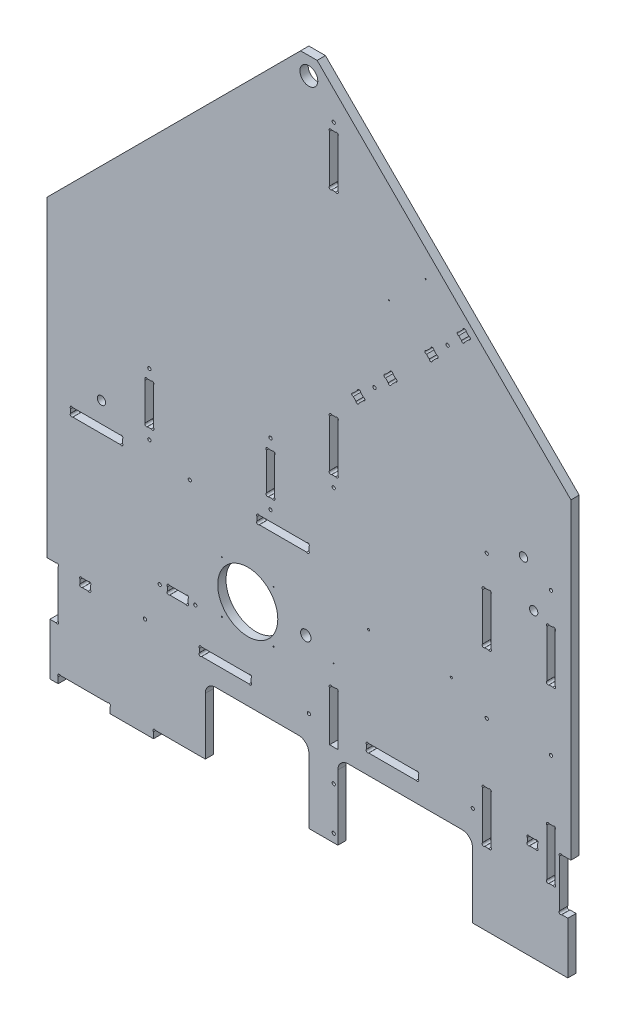
SolidWorks part; units mm, degrees
ref_plane "Plan de face" through (0, 0, 0) normal (0, 0, 1) x (1, 0, 0)
ref_plane "Plan de dessus" through (0, 0, 0) normal (0, 1, 0) x (1, 0, 0)
ref_plane "Plan de droite" through (0, 0, 0) normal (1, 0, 0) x (0, 0, -1)
sketch "Esquisse2" plane through (0, 0, 0) normal (0, 0, 1) x (1, 0, 0)
  line L0 (8, 626.5822) -> (-242, 376.5822) construction
  line L1 (-242, 376.5822) -> (-242, 76.5822) construction
  line L2 (-242, -23.4178) -> (258, -23.4178)
  line L3 (258, -23.4178) -> (258, 26.5822)
  line L4 (258, 376.5822) -> (8, 626.5822) construction
  line L5 (-268.5907, 76.5822) -> (316.4894, 76.5822) construction
  line L6 (-234, 74.4609) -> (-234, 28.7035)
  line L7 (-236.1213, 76.5822) -> (-242, 76.5822)
  line L8 (-236.1213, 26.5822) -> (-242, 26.5822)
  line L9 (-242, 26.5822) -> (-242, -23.4178)
  line L10 (-242, 76.5822) -> (-245, 76.5822)
  line L11 (252.1213, 26.5822) -> (258, 26.5822)
  line L12 (250, 74.4609) -> (250, 28.7035)
  line L13 (252.1213, 76.5822) -> (258, 76.5822)
  line L14 (258, 76.5822) -> (258, 376.5822) construction
  line L15 (-245, 76.5822) -> (-245, 377.8249)
  line L16 (8, 626.5822) -> (5.8787, 628.7035) construction
  line L17 (5.8787, 628.7035) -> (-245, 377.8249) construction
  line L18 (-245, 377.8249) -> (8, 630.8249)
  line L19 (258, 76.5822) -> (261, 76.5822)
  line L20 (261, 76.5822) -> (261, 377.8249)
  line L21 (8, 626.5822) -> (10.1213, 628.7035) construction
  line L22 (10.1213, 628.7035) -> (261, 377.8249) construction
  line L23 (261, 377.8249) -> (8, 630.8249)
  line L24 (-150, 274.5822) -> (-150, 234.5822) construction
  line L25 (-147.8787, 274.5822) -> (-144.1213, 274.5822)
  line L26 (-150, 272.4609) -> (-150, 236.7035)
  line L27 (-147.8787, 234.5822) -> (-144.1213, 234.5822)
  line L28 (-142, 272.4609) -> (-142, 236.7035)
  line L29 (-150, 274.5822) -> (-142, 274.5822) construction
  line L30 (-150, 234.5822) -> (-142, 234.5822) construction
  line L31 (-25, 274.5822) -> (-25, 234.5822) construction
  line L32 (-27.1213, 274.5822) -> (-30.8787, 274.5822)
  line L33 (-25, 272.4609) -> (-25, 236.7035)
  line L34 (-27.1213, 234.5822) -> (-30.8787, 234.5822)
  line L35 (-33, 272.4609) -> (-33, 236.7035)
  line L36 (-33, 274.5822) -> (-33, 234.5822) construction
  line L37 (163.925, 463.9178) -> (120.0844, 431.3909) construction
  line L38 (49.3737, 360.6803) -> (93.2143, 393.2072) construction
  line L39 (245.7307, 212.5822) -> (237.7307, 96.5822) construction
  line L40 (183.7307, 212.5822) -> (175.7307, 96.5822) construction
  line L41 (223.0384, 268.2822) -> (227.1201, 266.2822) construction
  arc A0 (-234, 74.4609) -> (-236.1213, 76.5822) centre (-235.0607, 75.5216) ccw
  arc A1 (-236.1213, 26.5822) -> (-234, 28.7035) centre (-235.0607, 27.6429) ccw
  arc A2 (252.1213, 26.5822) -> (250, 28.7035) centre (251.0607, 27.6429) cw
  arc A3 (250, 74.4609) -> (252.1213, 76.5822) centre (251.0607, 75.5216) cw
  arc A4 (-27.1213, 234.5822) -> (-25, 236.7035) centre (-26.0607, 235.6429) ccw
  arc A5 (-25, 272.4609) -> (-27.1213, 274.5822) centre (-26.0607, 273.5216) ccw
  arc A6 (-30.8787, 274.5822) -> (-33, 272.4609) centre (-31.9393, 273.5216) ccw
  arc A7 (-33, 236.7035) -> (-30.8787, 234.5822) centre (-31.9393, 235.6429) ccw
  arc A8 (-147.8787, 274.5822) -> (-150, 272.4609) centre (-148.9393, 273.5216) ccw
  arc A9 (-144.1213, 234.5822) -> (-142, 236.7035) centre (-143.0607, 235.6429) ccw
  arc A10 (-150, 236.7035) -> (-147.8787, 234.5822) centre (-148.9393, 235.6429) ccw
  arc A11 (-142, 272.4609) -> (-144.1213, 274.5822) centre (-143.0607, 273.5216) ccw
  circle A12 centre (-29, 284.5822) radius 1.55
  circle A13 centre (-29, 224.5822) radius 1.55
  circle A14 centre (-146, 284.0822) radius 1.55
  circle A15 centre (-146, 224.5822) radius 1.55
  circle A16 centre (-101.6159, 108.5822) radius 1.55
  circle A17 centre (-136, 108.5822) radius 1.55
  circle A19 centre (225.0793, 267.2822) radius 4
  circle A23 centre (142.0047, 447.6544) radius 1.55
  circle A24 centre (71.294, 376.9437) radius 1.55
  circle A29 centre (241.7307, 154.5822) radius 1.55
  circle A30 centre (179.7307, 154.5822) radius 1.55
  dimension "D2" = 650
  dimension "D4" = 50
  dimension "D6" = 1.5
  dimension "D7" = 1.5
  dimension "D1" = 100
  dimension "D3" = 500
  dimension "D8" = 8
  dimension "D9" = 8
  dimension "D10" = 0
  dimension "D11" = 0
  dimension "D12" = 0
  dimension "D13" = 0
  dimension "D14" = 0
extrude "Boss.-Extru.1" add sketch "Esquisse2" along normal blind 8
sketch "Esquisse3" plane through (0, 0, 8) normal (0, 0, 1) x (1, 0, 0)
  line L0 (-117, 501.5822) -> (8, 376.5822) construction
  line L1 (25.7058, 481.3683) -> (25.7058, 606.6018) construction
  line L2 (30, 604.6018) -> (30, 596.1432) construction
  line L3 (8, 630.8249) -> (8, -42.6778) construction
  line L4 (121.6863, 497.3396) -> (-14.463, 361.1903) construction
  line L5 (158.8094, 475.7728) -> (106.9524, 423.9159) construction
  line L6 (106.9524, 423.9159) -> (44.0813, 361.0447) construction
  line L7 (44.0813, 361.0447) -> (16.8577, 388.2684) construction
  line L8 (136.0178, 441.6675) -> (53.2863, 358.936) construction
  line L9 (50.4578, 361.7644) -> (56.1147, 356.1076) construction
  line L10 (136.0178, 441.6675) -> (164.4663, 470.116) construction
  line L11 (138.8462, 438.8391) -> (56.1147, 356.1076) construction
  line L12 (138.8462, 438.8391) -> (167.2947, 467.2875) construction
  line L13 (50.4578, 361.7644) -> (161.6378, 472.9444) construction
  line L14 (124.2412, 427.2341) -> (121.5844, 429.8909)
  line L15 (162.425, 462.4178) -> (158.3539, 458.3468)
  line L16 (155.3539, 458.3468) -> (152.6971, 461.0036)
  line L17 (144.8331, 444.826) -> (136.3478, 453.3112) construction
  line L18 (152.6971, 464.0036) -> (156.7681, 468.0747)
  line L19 (159.7681, 468.0747) -> (162.425, 465.4178)
  line L20 (125.6554, 436.962) -> (121.5844, 432.8909)
  line L21 (131.3123, 434.3051) -> (128.6554, 436.962)
  line L22 (127.2412, 427.2341) -> (131.3123, 431.3051)
  line L23 (65.6371, 382.6006) -> (74.1224, 374.1153) construction
  line L24 (56.5305, 356.5234) -> (60.6016, 360.5945)
  line L25 (84.6432, 387.6361) -> (81.9864, 390.2929)
  line L26 (81.9864, 393.2929) -> (86.0574, 397.364)
  line L27 (89.0574, 397.364) -> (91.7143, 394.7072)
  line L28 (0, 622.8249) -> (16, 622.8249)
  line L29 (8, 630.8249) -> (-245, 377.8249) construction
  line L30 (16, 622.8249) -> (8, 630.8249)
  line L31 (49.5, 481.3683) -> (-92.9948, 481.3683) construction
  line L32 (36, 509.4867) -> (36, 448.3117) construction
  line L33 (91.7143, 391.7072) -> (87.6432, 387.6361)
  line L34 (50.8737, 359.1803) -> (53.5305, 356.5234)
  line L35 (54.9447, 366.2513) -> (50.8737, 362.1803)
  line L36 (60.6016, 363.5945) -> (57.9447, 366.2513)
  line L37 (36, -23.4178) -> (36, 39.5822)
  line L38 (-234, -15.4178) -> (-112, -15.4178) construction
  line L39 (46, 49.5822) -> (156, 49.5822)
  line L40 (166, 39.5822) -> (166, -23.4178)
  line L41 (-242, -23.4178) -> (258, -23.4178) construction
  line L42 (166, -23.4178) -> (36, -23.4178)
  line L43 (245.7307, 46.5822) -> (245.7307, 260.1538) construction
  line L44 (245.7307, 302.5822) -> (175.7307, 302.5822) construction
  line L45 (175.7307, 302.5822) -> (175.7307, 46.5822) construction
  line L46 (36, -23.4178) -> (28, -23.4178) construction
  line L47 (-234, 156.5822) -> (-234, -15.4178) construction
  line L48 (16.8577, 388.2684) -> (133.7071, 505.1178) construction
  line L49 (-112, -15.4178) -> (-112, 156.5822) construction
  line L50 (8, -23.4178) -> (8, 39.5822)
  line L51 (-2, 49.5822) -> (-82, 49.5822)
  line L52 (-92, 39.5822) -> (-92, -15.4178)
  line L53 (-92, -23.4178) -> (8, -23.4178)
  line L54 (28, -23.4178) -> (28, 596.1432) construction
  line L55 (36, 521.5822) -> (28, 521.5822) construction
  line L56 (36, 446.5822) -> (28, 446.5822) construction
  line L57 (36, 381.5822) -> (28, 381.5822) construction
  line L58 (149.3825, 499.5799) -> (-10.1278, 340.0696) construction
  line L59 (28, 56.5822) -> (36, 56.5822)
  line L60 (28, 56.5822) -> (28, 104.4609)
  line L61 (30.1213, 106.5822) -> (33.714, 106.5822)
  line L62 (36, 104.4609) -> (36, 56.5822)
  line L63 (28, 106.5822) -> (31.8505, 102.7317) construction
  line L64 (31.8505, 102.7317) -> (36, 106.5822) construction
  line L65 (30.1213, 521.5822) -> (33.8787, 521.5822)
  line L66 (36, 523.7035) -> (36, 569.4609)
  line L67 (33.8787, 571.5822) -> (30.1213, 571.5822)
  line L68 (28, 569.4609) -> (28, 523.7035)
  line L69 (36, 283.5822) -> (28, 283.5822) construction
  line L70 (30.1213, 283.5822) -> (33.8787, 283.5822)
  line L71 (36, 285.7035) -> (36, 331.4609)
  line L72 (33.8787, 333.5822) -> (30.1213, 333.5822)
  line L73 (28, 331.4609) -> (28, 285.7035)
  line L74 (28, 333.5822) -> (32, 333.5822) construction
  line L75 (175.7307, 46.5822) -> (245.7307, 46.5822) construction
  line L76 (242.7592, 46.5822) -> (240.7023, 46.5822) construction
  line L77 (245.7307, 48.7035) -> (245.7307, 94.4609) construction
  line L78 (210.7307, 212.5822) -> (175.7307, 212.5822) construction
  line L79 (243.6094, 212.5822) -> (239.8521, 212.5822)
  line L80 (220.9721, 76.5822) -> (226.7294, 76.5822)
  line L81 (218.8507, 74.4609) -> (218.8507, 70.7035)
  line L82 (237.7307, 218.4818) -> (237.7307, 262.5822) construction
  line L83 (240.7592, 266.3605) -> (244.5166, 266.3605) construction
  line L84 (245.7307, 260.1538) -> (245.7307, 218.4818) construction
  line L85 (210.7307, 302.5822) -> (210.7307, 46.5822) construction
  line L86 (239.8521, 262.5822) -> (243.3024, 262.5822)
  line L87 (181.6094, 212.5822) -> (177.8521, 212.5822)
  line L88 (237.7307, 260.4609) -> (237.7307, 214.7035)
  line L89 (220.9721, 68.5822) -> (226.7294, 68.5822)
  line L90 (228.8507, 74.4609) -> (228.8507, 70.7035)
  line L91 (-192.25, 227.5756) -> (-192.25, 260.1538) construction
  line L92 (175.7307, 48.7035) -> (175.7307, 94.4609) construction
  line L93 (178.7023, 46.5822) -> (180.7592, 46.5822) construction
  line L94 (179.7307, 302.5822) -> (179.7307, 46.5822) construction
  line L95 (241.7307, 46.5822) -> (241.7307, 302.5822) construction
  line L96 (245.7307, 260.1538) -> (245.7307, 214.7035)
  line L97 (175.7307, 260.1538) -> (175.7307, 214.7035)
  line L98 (181.6094, 262.5822) -> (178.1591, 262.5822)
  line L99 (183.7307, 260.4609) -> (183.7307, 214.7035)
  line L100 (179.7307, 174.5822) -> (241.7307, 174.5822) construction
  line L101 (32, -23.4178) -> (32, 596.1432) construction
  line L102 (-234, 156.5822) -> (-234, 164.5822) construction
  line L103 (-234, 164.5822) -> (-112, 164.5822) construction
  line L104 (-112, 164.5822) -> (-112, 156.5822) construction
  line L105 (261, 76.5822) -> (-245, 76.5822) construction
  line L106 (261, 377.8249) -> (8, 630.8249) construction
  line L107 (-222, 212.4609) -> (-222, 208.7035)
  line L108 (-219.8787, 214.5822) -> (-174.1213, 214.5822)
  line L109 (-172, 212.4609) -> (-172, 208.7035)
  line L110 (-174.1213, 206.5822) -> (-219.8787, 206.5822)
  line L111 (8, 212.4609) -> (8, 208.7035)
  line L112 (5.8787, 214.5822) -> (-39.8787, 214.5822)
  line L113 (-42, 212.4609) -> (-42, 208.7035)
  line L114 (-39.8787, 206.5822) -> (5.8787, 206.5822)
  line L115 (-76, 166.5822) -> (-76, 106.5822) construction
  line L116 (-234, -23.4178) -> (-234, -17.5391)
  line L117 (-231.8787, -15.4178) -> (-186.1213, -15.4178)
  line L118 (-184, -17.5391) -> (-184, -23.4178)
  line L119 (-242, 26.5822) -> (-242, -23.4178) construction
  line L120 (-92, -15.4178) -> (-139.8787, -15.4178)
  line L121 (-142, -17.5391) -> (-142, -23.4178)
  line L122 (-142, -23.4178) -> (-92, -23.4178)
  line L123 (-184, -23.4178) -> (-234, -23.4178)
  line L124 (-81, 136.5822) -> (-21, 136.5822) construction
  line L125 (-81, 166.5822) -> (-21, 166.5822) construction
  line L126 (-81, 166.5822) -> (-81, 106.5822) construction
  line L127 (-81, 106.5822) -> (-21, 106.5822) construction
  line L128 (-21, 166.5822) -> (-21, 106.5822) construction
  line L129 (-51, 166.5822) -> (-51, 106.5822) construction
  line L130 (-81, 161.5822) -> (-21, 161.5822) construction
  line L131 (28, 596.1432) -> (28, 606.6018) construction
  line L132 (28, 596.1432) -> (32, 596.1432) construction
  line L133 (32, 596.1432) -> (32, 602.6018) construction
  line L134 (8, 630.8249) -> (8, 580.8249) construction
  line L135 (32, 602.6018) -> (28, 606.6018) construction
  line L136 (65.7875, 76.5822) -> (111.5449, 76.5822)
  line L137 (113.6662, 74.4609) -> (113.6662, 70.7035)
  line L138 (111.5449, 68.5822) -> (65.7875, 68.5822)
  line L139 (63.6662, 70.7035) -> (63.6662, 74.4609)
  line L140 (-47.6662, 70.7035) -> (-47.6662, 74.4609)
  line L141 (-95.5449, 68.5822) -> (-49.7875, 68.5822)
  line L142 (-97.6662, 74.4609) -> (-97.6662, 70.7035)
  line L143 (-49.7875, 76.5822) -> (-95.5449, 76.5822)
  line L144 (-212.8507, 74.4609) -> (-212.8507, 70.7035)
  line L145 (220.9721, 76.5822) -> (226.7294, 76.5822) construction
  line L146 (218.8507, 74.4609) -> (218.8507, 70.7035) construction
  line L147 (220.9721, 68.5822) -> (226.7294, 68.5822) construction
  line L148 (228.8507, 74.4609) -> (228.8507, 70.7035) construction
  line L149 (-204.9721, 68.5822) -> (-210.7294, 68.5822)
  line L150 (-202.8507, 74.4609) -> (-202.8507, 70.7035)
  line L151 (-204.9721, 76.5822) -> (-210.7294, 76.5822)
  line L152 (-245, 377.8249) -> (-245, 76.5822) construction
  line L153 (-172, 210.5822) -> (-42, 210.5822) construction
  line L154 (-202.8507, 72.5822) -> (-97.6662, 72.5822) construction
  line L155 (-97.6662, 72.5822) -> (-47.6662, 72.5822) construction
  line L156 (-47.6662, 72.5822) -> (63.6662, 72.5822) construction
  line L157 (63.6662, 72.5822) -> (218.8507, 72.5822) construction
  line L158 (8, 630.8249) -> (0, 622.8249)
  line L159 (181.6094, 46.5822) -> (177.8521, 46.5822)
  line L160 (239.8521, 96.5822) -> (243.6094, 96.5822)
  line L161 (237.7307, 94.4609) -> (237.7307, 48.7035)
  line L162 (239.8521, 46.5822) -> (243.6094, 46.5822)
  line L163 (245.7307, 94.4609) -> (245.7307, 48.7035)
  line L164 (175.7307, 94.4609) -> (175.7307, 48.7035)
  line L165 (181.6094, 96.5822) -> (177.8521, 96.5822)
  line L166 (183.7307, 94.4609) -> (183.7307, 48.7035)
  line L167 (245.7307, 262.5822) -> (245.7307, 302.5822) construction
  line L168 (-95.2925, 112.5822) -> (-106.3787, 112.5822) construction
  line L169 (-126.3787, 112.5822) -> (-110.6213, 112.5822)
  line L170 (-128.5, 110.4609) -> (-128.5, 106.7035)
  line L171 (-126.3787, 104.5822) -> (-110.6213, 104.5822)
  line L172 (-108.5, 110.4609) -> (-108.5, 106.7035)
  line L173 (-143.5, 112.5822) -> (-143.5, 104.5822) construction
  arc A0 (159.7681, 468.0747) -> (156.7681, 468.0747) centre (158.2681, 468.0747) ccw
  arc A1 (162.425, 465.4178) -> (162.425, 462.4178) centre (162.425, 463.9178) cw
  arc A2 (152.6971, 464.0036) -> (152.6971, 461.0036) centre (152.6971, 462.5036) ccw
  arc A3 (155.3539, 458.3468) -> (158.3539, 458.3468) centre (156.8539, 458.3468) ccw
  arc A4 (131.3123, 434.3051) -> (131.3123, 431.3051) centre (131.3123, 432.8051) cw
  arc A5 (125.6554, 436.962) -> (128.6554, 436.962) centre (127.1554, 436.962) cw
  arc A6 (121.5844, 432.8909) -> (121.5844, 429.8909) centre (121.5844, 431.3909) ccw
  arc A7 (127.2412, 427.2341) -> (124.2412, 427.2341) centre (125.7412, 427.2341) cw
  arc A8 (89.0574, 397.364) -> (86.0574, 397.364) centre (87.5574, 397.364) ccw
  arc A9 (91.7143, 391.7072) -> (91.7143, 394.7072) centre (91.7143, 393.2072) ccw
  arc A10 (81.9864, 393.2929) -> (81.9864, 390.2929) centre (81.9864, 391.7929) ccw
  arc A11 (84.6432, 387.6361) -> (87.6432, 387.6361) centre (86.1432, 387.6361) ccw
  arc A12 (60.6016, 363.5945) -> (60.6016, 360.5945) centre (60.6016, 362.0945) cw
  arc A13 (54.9447, 366.2513) -> (57.9447, 366.2513) centre (56.4447, 366.2513) cw
  arc A14 (56.5305, 356.5234) -> (53.5305, 356.5234) centre (55.0305, 356.5234) cw
  arc A15 (50.8737, 359.1803) -> (50.8737, 362.1803) centre (50.8737, 360.6803) cw
  circle A16 centre (120.815, 492.2256) radius 0.5
  circle A17 centre (85.4596, 456.8703) radius 0.5
  circle A18 centre (65.4807, 171.5822) radius 1
  arc A19 (30.1213, 106.5822) -> (28, 104.4609) centre (29.0607, 105.5216) ccw
  arc A20 (36, 104.4609) -> (33.714, 106.5822) centre (34.857, 105.5216) ccw
  arc A21 (30.1213, 571.5822) -> (28, 569.4609) centre (29.0607, 570.5216) ccw
  arc A22 (36, 569.4609) -> (33.8787, 571.5822) centre (34.9393, 570.5216) ccw
  arc A23 (28, 523.7035) -> (30.1213, 521.5822) centre (29.0607, 522.6429) ccw
  arc A24 (33.8787, 521.5822) -> (36, 523.7035) centre (34.9393, 522.6429) ccw
  arc A25 (30.1213, 333.5822) -> (28, 331.4609) centre (29.0607, 332.5216) ccw
  arc A26 (36, 331.4609) -> (33.8787, 333.5822) centre (34.9393, 332.5216) ccw
  arc A27 (28, 285.7035) -> (30.1213, 283.5822) centre (29.0607, 284.6429) ccw
  arc A28 (33.8787, 283.5822) -> (36, 285.7035) centre (34.9393, 284.6429) ccw
  arc A29 (239.8521, 262.5822) -> (237.7307, 260.4609) centre (238.7914, 261.5216) ccw
  arc A30 (245.7307, 260.1538) -> (243.3024, 262.5822) centre (244.5166, 261.368) ccw
  arc A31 (237.7307, 214.7035) -> (239.8521, 212.5822) centre (238.7914, 213.6429) ccw
  arc A32 (243.6094, 212.5822) -> (245.7307, 214.7035) centre (244.6701, 213.6429) ccw
  arc A33 (181.6094, 262.5822) -> (183.7307, 260.4609) centre (182.6701, 261.5216) cw
  arc A34 (175.7307, 260.1538) -> (178.1591, 262.5822) centre (176.9449, 261.368) cw
  arc A35 (177.8521, 212.5822) -> (175.7307, 214.7035) centre (176.7914, 213.6429) cw
  arc A36 (183.7307, 214.7035) -> (181.6094, 212.5822) centre (182.6701, 213.6429) cw
  arc A37 (245.7307, 94.4609) -> (243.6094, 96.5822) centre (244.6701, 95.5216) ccw
  arc A38 (239.8521, 96.5822) -> (237.7307, 94.4609) centre (238.7914, 95.5216) ccw
  arc A39 (237.7307, 48.7035) -> (239.8521, 46.5822) centre (238.7914, 47.6429) ccw
  arc A40 (243.6094, 46.5822) -> (245.7307, 48.7035) centre (244.6701, 47.6429) ccw
  arc A41 (175.7307, 94.4609) -> (177.8521, 96.5822) centre (176.7914, 95.5216) cw
  arc A42 (181.6094, 96.5822) -> (183.7307, 94.4609) centre (182.6701, 95.5216) cw
  arc A43 (177.8521, 46.5822) -> (175.7307, 48.7035) centre (176.7914, 47.6429) cw
  arc A44 (183.7307, 48.7035) -> (181.6094, 46.5822) centre (182.6701, 47.6429) cw
  circle A45 centre (179.7307, 292.5822) radius 1.55
  circle A46 centre (241.7307, 292.5822) radius 1.55
  circle A47 centre (179.7307, 174.5822) radius 0.5 construction
  circle A48 centre (241.7307, 174.5822) radius 0.5 construction
  circle A49 centre (32, 126.5822) radius 0.5
  circle A50 centre (32, 579.0822) radius 1.55
  circle A51 centre (32, 25.9979) radius 1.55
  circle A52 centre (32, -15.4178) radius 1.55
  arc A53 (-219.8787, 214.5822) -> (-222, 212.4609) centre (-220.9393, 213.5216) ccw
  arc A54 (-222, 208.7035) -> (-219.8787, 206.5822) centre (-220.9393, 207.6429) ccw
  arc A55 (-174.1213, 206.5822) -> (-172, 208.7035) centre (-173.0607, 207.6429) ccw
  arc A56 (-172, 212.4609) -> (-174.1213, 214.5822) centre (-173.0607, 213.5216) ccw
  arc A57 (-39.8787, 214.5822) -> (-42, 212.4609) centre (-40.9393, 213.5216) ccw
  arc A58 (8, 212.4609) -> (5.8787, 214.5822) centre (6.9393, 213.5216) ccw
  arc A59 (5.8787, 206.5822) -> (8, 208.7035) centre (6.9393, 207.6429) ccw
  arc A60 (-42, 208.7035) -> (-39.8787, 206.5822) centre (-40.9393, 207.6429) ccw
  arc A61 (-231.8787, -15.4178) -> (-234, -17.5391) centre (-232.9393, -16.4784) ccw
  arc A62 (-184, -17.5391) -> (-186.1213, -15.4178) centre (-185.0607, -16.4784) ccw
  arc A63 (-139.8787, -15.4178) -> (-142, -17.5391) centre (-140.9393, -16.4784) ccw
  circle A64 centre (-51, 136.5822) radius 29
  circle A65 centre (-76, 161.5822) radius 0.5
  circle A66 centre (-26, 161.5822) radius 0.5
  circle A67 centre (-26, 111.5822) radius 0.5
  circle A68 centre (-76, 111.5822) radius 0.5
  circle A69 centre (5, 136.5822) radius 5
  circle A70 centre (8, 605.8249) radius 8.625
  arc A71 (63.6662, 70.7035) -> (65.7875, 68.5822) centre (64.7269, 69.6429) ccw
  arc A72 (65.7875, 76.5822) -> (63.6662, 74.4609) centre (64.7269, 75.5216) ccw
  arc A73 (113.6662, 74.4609) -> (111.5449, 76.5822) centre (112.6055, 75.5216) ccw
  arc A74 (111.5449, 68.5822) -> (113.6662, 70.7035) centre (112.6055, 69.6429) ccw
  arc A75 (-95.5449, 68.5822) -> (-97.6662, 70.7035) centre (-96.6055, 69.6429) cw
  arc A76 (-97.6662, 74.4609) -> (-95.5449, 76.5822) centre (-96.6055, 75.5216) cw
  arc A77 (-49.7875, 76.5822) -> (-47.6662, 74.4609) centre (-48.7269, 75.5216) cw
  arc A78 (-47.6662, 70.7035) -> (-49.7875, 68.5822) centre (-48.7269, 69.6429) cw
  arc A79 (220.9721, 76.5822) -> (218.8507, 74.4609) centre (219.9114, 75.5216) ccw construction
  arc A80 (228.8507, 74.4609) -> (226.7294, 76.5822) centre (227.7901, 75.5216) ccw construction
  arc A81 (226.7294, 68.5822) -> (228.8507, 70.7035) centre (227.7901, 69.6429) ccw construction
  arc A82 (218.8507, 70.7035) -> (220.9721, 68.5822) centre (219.9114, 69.6429) ccw construction
  arc A83 (-202.8507, 70.7035) -> (-204.9721, 68.5822) centre (-203.9114, 69.6429) cw
  arc A84 (-210.7294, 68.5822) -> (-212.8507, 70.7035) centre (-211.7901, 69.6429) cw
  arc A85 (-212.8507, 74.4609) -> (-210.7294, 76.5822) centre (-211.7901, 75.5216) cw
  arc A86 (-204.9721, 76.5822) -> (-202.8507, 74.4609) centre (-203.9114, 75.5216) cw
  circle A87 centre (215.2318, 307.2604) radius 4
  circle A88 centre (-107, 210.5822) radius 1.55
  circle A89 centre (32, 273.5109) radius 1.55
  circle A90 centre (8, 72.5822) radius 1.55
  circle A91 centre (-150.2585, 72.5822) radius 1.55
  arc A92 (220.9721, 76.5822) -> (218.8507, 74.4609) centre (219.9114, 75.5216) ccw
  arc A93 (228.8507, 74.4609) -> (226.7294, 76.5822) centre (227.7901, 75.5216) ccw
  arc A94 (226.7294, 68.5822) -> (228.8507, 70.7035) centre (227.7901, 69.6429) ccw
  arc A95 (218.8507, 70.7035) -> (220.9721, 68.5822) centre (219.9114, 69.6429) ccw
  circle A96 centre (-192.25, 234.3823) radius 4
  arc A97 (-126.3787, 112.5822) -> (-128.5, 110.4609) centre (-127.4393, 111.5216) ccw
  arc A98 (-128.5, 106.7035) -> (-126.3787, 104.5822) centre (-127.4393, 105.6429) ccw
  arc A99 (-108.5, 110.4609) -> (-110.6213, 112.5822) centre (-109.5607, 111.5216) ccw
  arc A100 (-110.6213, 104.5822) -> (-108.5, 106.7035) centre (-109.5607, 105.6429) ccw
  circle A101 centre (145.4807, 171.5822) radius 1
  circle A102 centre (166.2585, 72.5822) radius 1.55
  arc A103 (156, 49.5822) -> (166, 39.5822) centre (156, 39.5822) cw
  arc A104 (36, 39.5822) -> (46, 49.5822) centre (46, 39.5822) cw
  arc A105 (8, 39.5822) -> (-2, 49.5822) centre (-2, 39.5822) ccw
  arc A106 (-82, 49.5822) -> (-92, 39.5822) centre (-82, 39.5822) ccw
  point P409 (166, 49.5822)
  point P416 (36, 49.5822)
  point P419 (8, 49.5822)
  point P422 (-92, 49.5822)
  dimension "D3" = 4
  dimension "D5" = 3
  dimension "D7" = 60
  dimension "D8" = 3
  dimension "D9" = 13.5
  dimension "D10" = 4
  dimension "D11" = 50
  dimension "D12" = 8
  dimension "D13" = 545
  dimension "D14" = 75
  dimension "D15" = 140
  dimension "D16" = 52.75
  dimension "D17" = 23.5
  dimension "D18" = 100
  dimension "D19" = 80
  dimension "D20" = 307
  dimension "D21" = 73
  dimension "D22" = 50
  dimension "D4" = 4
  dimension "D23" = 100
  dimension "D24" = 122
  dimension "D26" = 10
  dimension "D27" = 59
  dimension "D29" = 7.5
  dimension "D30" = 73
  dimension "D33" = 8
  dimension "D34" = 5
  dimension "D38" = 226
  dimension "D39" = 62
  dimension "D40" = 4
  dimension "D41" = 116
  dimension "D42" = 8
  dimension "D47" = 10
  dimension "D50" = 17.25
  dimension "D52" = 130
  dimension "D53" = 10
  dimension "D6" = 60
  dimension "D25" = 50
  dimension "D28" = 3
  dimension "D31" = 50
  dimension "D32" = 20
  dimension "D35" = 60
  dimension "D36" = 60
  dimension "D37" = 5
  dimension "D43" = 20
  dimension "D44" = 3
  dimension "D45" = 0
  dimension "D46" = 15
  dimension "D48" = 17
  dimension "D49" = 10
  dimension "D51" = 8
extrude "Enlèv. mat.-Extru.1" cut sketch "Esquisse3" against normal blind 8
